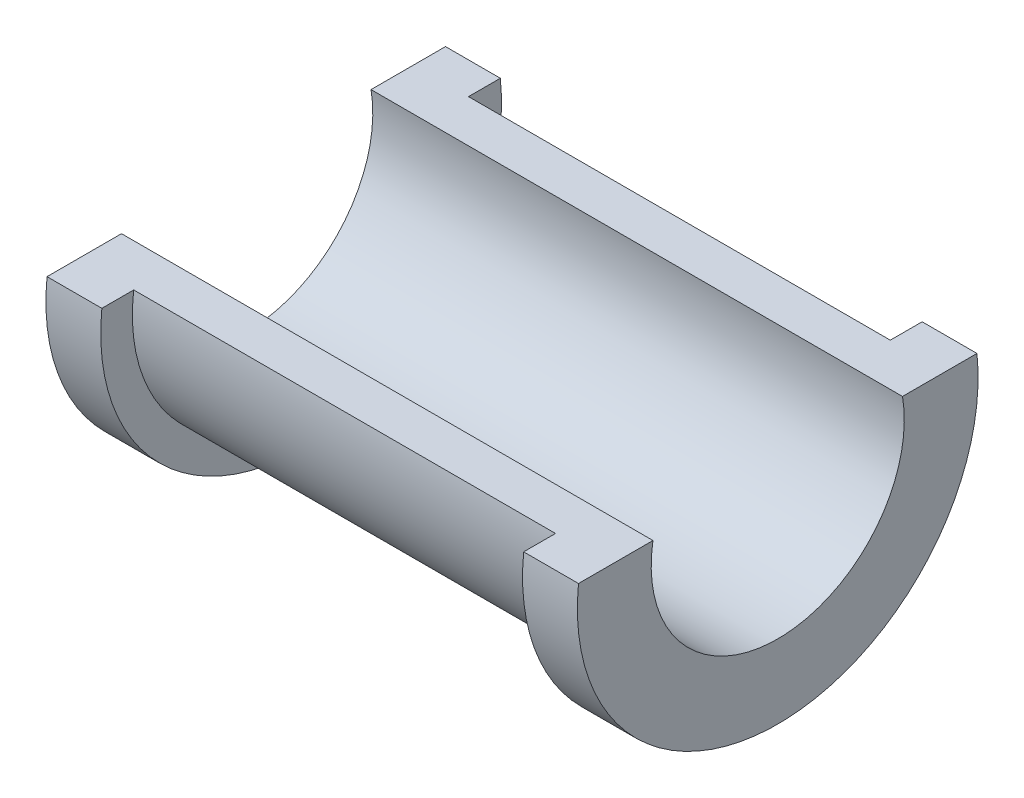
SolidWorks part; units mm, degrees
ref_plane "Front Plane" through (0, 0, 0) normal (0, 0, 1) x (1, 0, 0)
ref_plane "Top Plane" through (0, 0, 0) normal (0, 1, 0) x (1, 0, 0)
ref_plane "Right Plane" through (0, 0, 0) normal (1, 0, 0) x (0, 0, -1)
sketch "Sketch1" plane through (0, 0, 0) normal (0, 0, 1) x (1, 0, 0)
  line L0 (0, 0) -> (0, 47.5)
  line L1 (0, 47.5) -> (13, 47.5)
  line L2 (13, 47.5) -> (13, 40)
  line L3 (13, 40) -> (113, 40)
  line L4 (113, 40) -> (113, 47.5)
  line L5 (113, 47.5) -> (126, 47.5)
  line L6 (126, 47.5) -> (126, 0)
  line L7 (126, 0) -> (0, 0) construction
  line L8 (0, 0) -> (126, 0)
  dimension "D1" = 126
  dimension "D2" = 100
  dimension "D3" = 80
  dimension "D4" = 95
revolve "Revolve1" add sketch "Sketch1" angle 360 about L7
sketch "Sketch2" plane through (126, 0, 0) normal (1, 0, 0) x (0, 0, -1)
  circle A0 centre (0, 0) radius 30
  dimension "D1" = 60
extrude "Cut-Extrude1" cut sketch "Sketch2" against normal through all
ref_plane "Plane1" through (0, 43, 0) normal (0, 1, 0) x (1, 0, 0)
sketch "Sketch3" plane through (0, 43, 0) normal (0, 1, 0) x (1, 0, 0)
  line L0 (0, 47.5) -> (0, -47.5) construction
  circle A0 centre (63, 0) radius 8
  point P4 (0, 0)
  dimension "D1" = 16
  dimension "D2" = 63
extrude "Boss-Extrude1" add sketch "Sketch3" against normal up to next
hole_wizard "M10x1.0 Tapped Hole1" positions "Sketch4" profile "Sketch5" tap size "M10x1.0" standard "ANSI Metric"
sketch "Sketch4" plane through (0, 43, 0) normal (0, 1, 0) x (1, 0, 0)
  point P0 (63, 0)
sketch "Sketch5" plane through (63, 43, 0) normal (1, 0, 0) x (0, 0, 1)
  line L0 (0, 0) -> (0, 13)
  line L1 (0, 13) -> (4.5, 13)
  line L2 (4.5, 13) -> (4.5, 0)
  line L5 (4.5, 0) -> (0, 0)
  line L11 (0, -6.35) -> (0, 107.95) construction
  dimension "Thru Tap Drill Dia." = 9
  dimension "Thru Tap Drill Depth" = 13
sketch "Sketch6" plane through (126, 0, 0) normal (1, 0, 0) x (0, 0, -1)
  line L0 (-62.0855, 5) -> (59.6926, 5)
  dimension "D1" = 5
extrude "Cut-Extrude2" cut sketch "Sketch6" along normal through all and the other way through all contours L0
